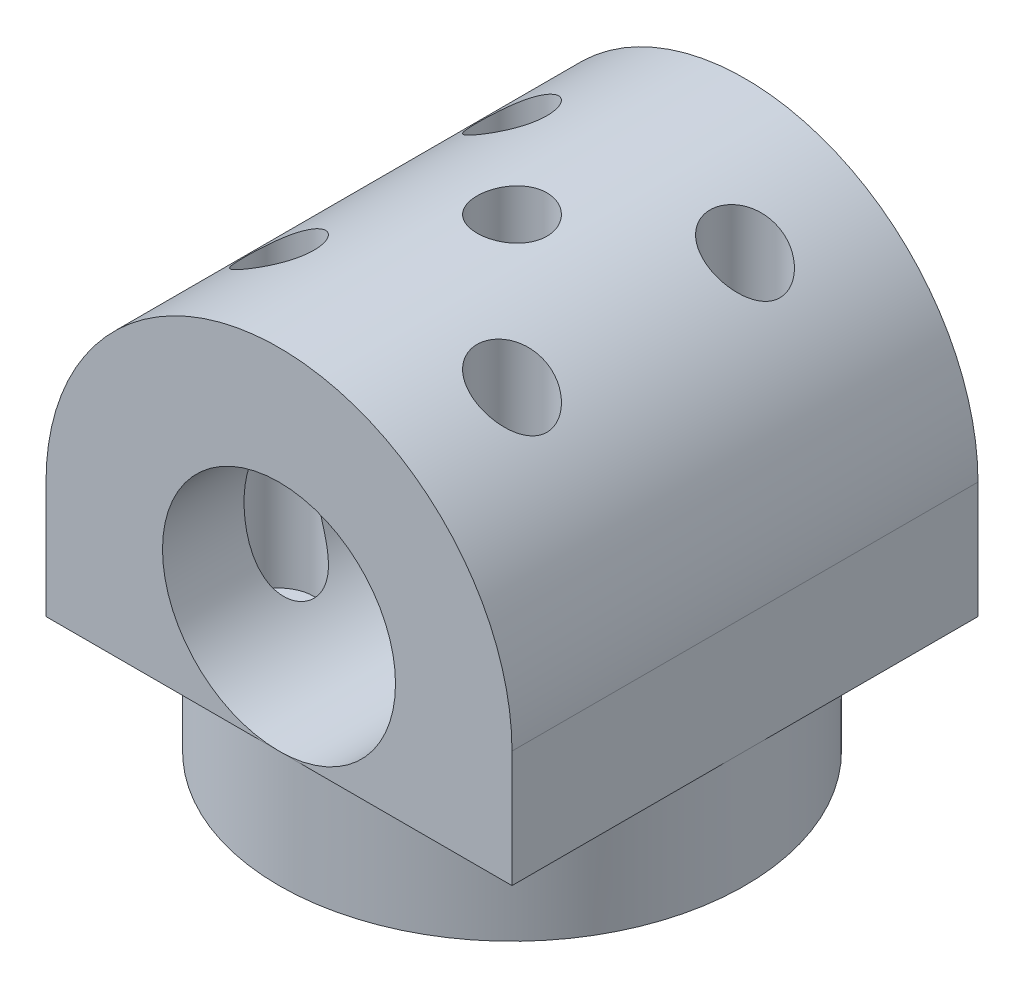
SolidWorks part; units mm, degrees
ref_plane "Ebene vorne" through (0, 0, 0) normal (0, 0, 1) x (1, 0, 0)
ref_plane "Ebene oben" through (0, 0, 0) normal (0, 1, 0) x (1, 0, 0)
ref_plane "Ebene rechts" through (0, 0, 0) normal (1, 0, 0) x (0, 0, -1)
sketch "Skizze1" plane through (0, 0, 0) normal (0, 1, 0) x (1, 0, 0)
  circle A0 centre (0, 0) radius 20
  dimension "D1" = 40
extrude "Aufsatz-Linear austragen1" add sketch "Skizze1" along normal blind 10
sketch "Skizze2" plane through (0, 0, 0) normal (0, 0, 1) x (1, 0, 0)
  line L0 (0, 0) -> (0, -50000) construction
  line L2 (20, 20) -> (20, 10)
  line L3 (20, 10) -> (-20, 10) construction
  line L4 (20, 10) -> (-20, 10)
  line L5 (-20, 10) -> (-20, 20)
  arc A0 (20, 20) -> (-20, 20) centre (0, 20) ccw
  dimension "D1" = 40
  dimension "D2" = 20
extrude "Aufsatz-Linear austragen2" add sketch "Skizze2" along normal mid plane 40
sketch "Skizze3" plane through (0, 0, 20) normal (0, 0, 1) x (1, 0, 0)
  circle A0 centre (0, 20) radius 10
  dimension "D1" = 20
extrude "Schnitt-Linear austragen1" cut sketch "Skizze3" against normal through all
sketch "Skizze4" plane through (0, 0, 0) normal (0, -1, 0) x (1, 0, 0)
  line L1 (10, 10) -> (-10, 10) construction
  line L2 (10, 10) -> (10, -10) construction
  line L3 (10, -10) -> (-10, -10) construction
  line L4 (-10, 10) -> (-10, -10) construction
  line L5 (10, 10) -> (-10, -10) construction
  line L6 (10, -10) -> (-10, 10) construction
  circle A0 centre (-10, 10) radius 1.575
  circle A1 centre (-10, -10) radius 1.575
  circle A2 centre (10, -10) radius 1.575
  circle A3 centre (10, 10) radius 1.575
  circle A4 centre (0, 0) radius 1.575
  point P0 (0, 0)
  dimension "D3" = 3.15
  dimension "D1" = 20
  dimension "D2" = 20
extrude "Schnitt-Linear austragen2" cut sketch "Skizze4" against normal through all
sketch "Skizze5" plane through (0, 10, 0) normal (0, 1, 0) x (1, 0, 0)
  circle A0 centre (-10, 10) radius 3
  circle A1 centre (-10, -10) radius 3
  circle A2 centre (0, 0) radius 3
  circle A3 centre (10, -10) radius 3
  circle A4 centre (10, 10) radius 3
  dimension "D1" = 6
extrude "Schnitt-Linear austragen3" cut sketch "Skizze5" along normal through all
sketch "Skizze6" plane through (0, 10, 0) normal (0, 1, 0) x (1, 0, 0)
  circle A0 centre (0, 0) radius 3
extrude "Schnitt-Linear austragen4" cut sketch "Skizze6" against normal blind 3
